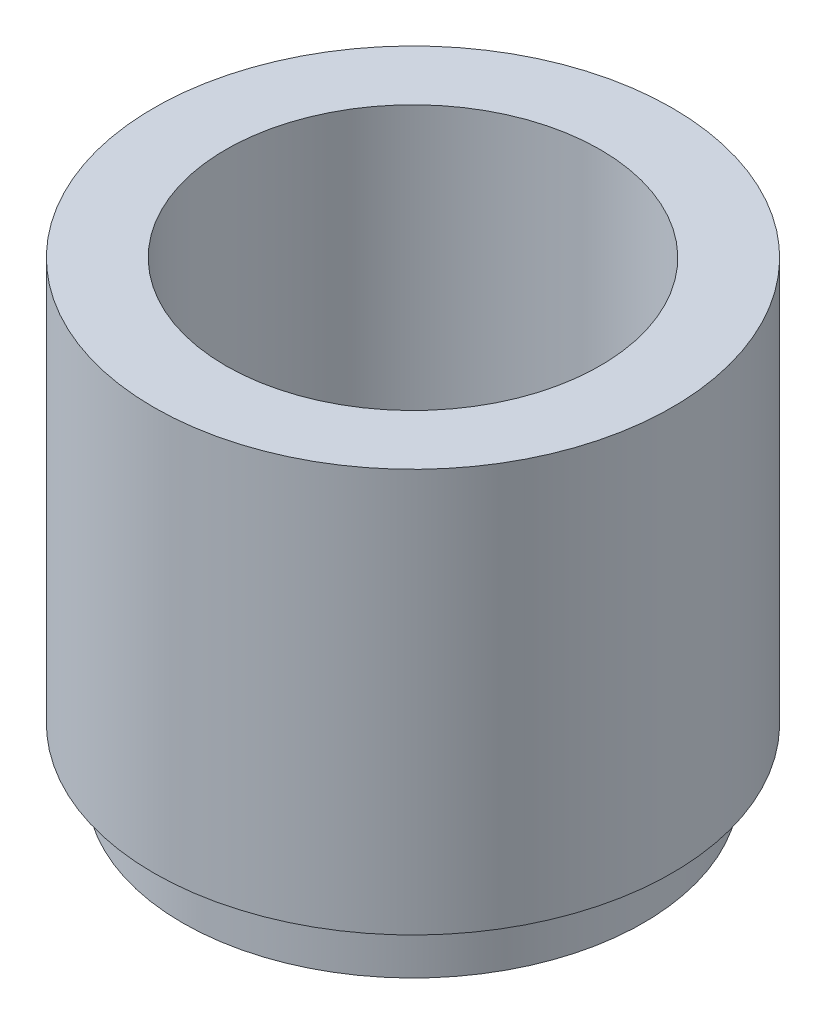
SolidWorks part; units mm, degrees
ref_plane "Front Plane" through (0, 0, 0) normal (0, 0, 1) x (1, 0, 0)
ref_plane "Top Plane" through (0, 0, 0) normal (0, 1, 0) x (1, 0, 0)
ref_plane "Right Plane" through (0, 0, 0) normal (1, 0, 0) x (0, 0, -1)
sketch "Sketch1" plane through (0, 0, 0) normal (0, 1, 0) x (1, 0, 0)
  circle A0 centre (0, 0) radius 45
  dimension "D1" = 90
extrude "Boss-Extrude1" add sketch "Sketch1" along normal blind 80
sketch "Sketch2" plane through (0, 0, 0) normal (0, -1, 0) x (1, 0, 0)
  circle A3 centre (0, 0) radius 40
  circle A4 centre (0, 0) radius 45
  dimension "D1" = 80
extrude "Cut-Extrude3" cut sketch "Sketch2" against normal blind 10
sketch "Sketch3" plane through (0, 0, 0) normal (0, -1, 0) x (1, 0, 0)
  circle A0 centre (0, 0) radius 32.5
  dimension "D1" = 65
extrude "Cut-Extrude4" cut sketch "Sketch3" against normal through all
